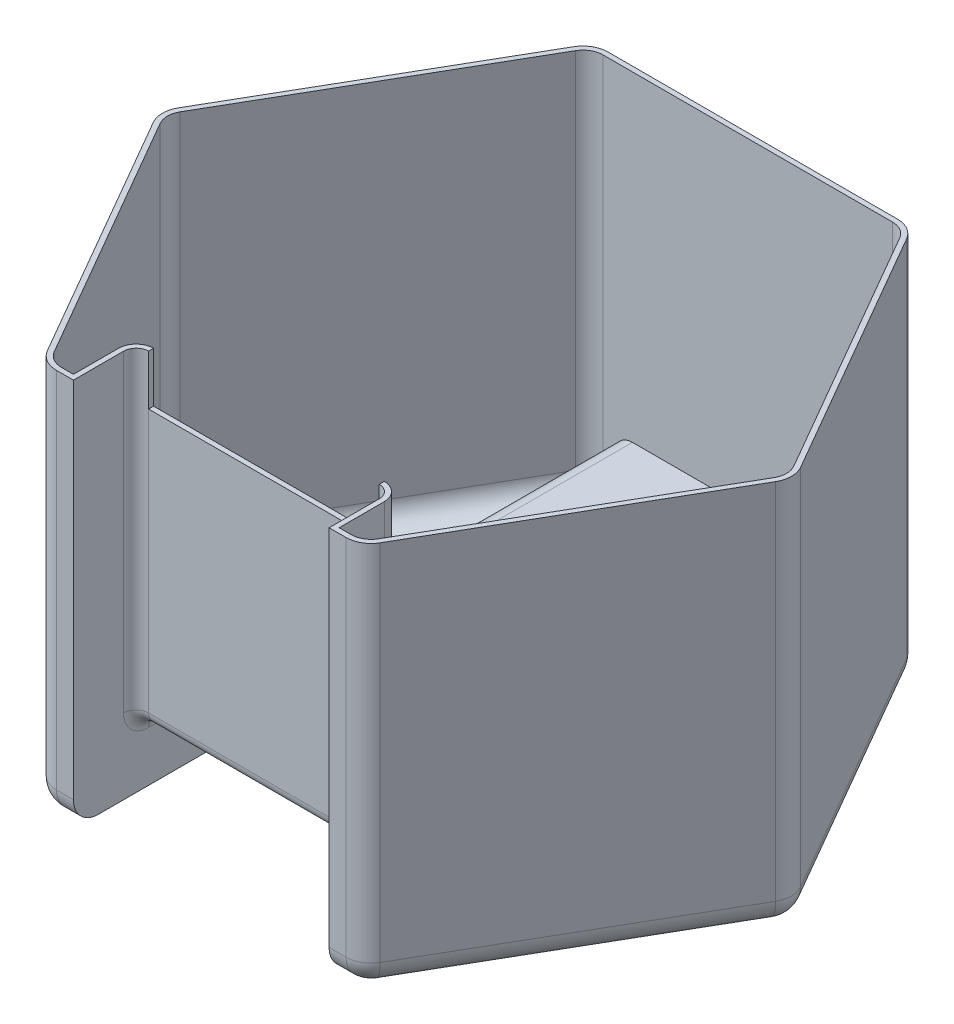
SolidWorks part; units mm, degrees
ref_plane "Front Plane" through (0, 0, 0) normal (0, 0, 1) x (1, 0, 0)
ref_plane "Top Plane" through (0, 0, 0) normal (0, 1, 0) x (1, 0, 0)
ref_plane "Right Plane" through (0, 0, 0) normal (1, 0, 0) x (0, 0, -1)
sketch "Sketch1" plane through (0, 0, 0) normal (0, 1, 0) x (1, 0, 0)
  line L1 (63.5085, 110) -> (-63.5085, 110)
  line L2 (-63.5085, 110) -> (-127.0171, 0)
  line L3 (-127.0171, 0) -> (-63.5085, -110)
  line L4 (-63.5085, -110) -> (63.5085, -110)
  line L5 (63.5085, -110) -> (127.0171, 0)
  line L6 (127.0171, 0) -> (63.5085, 110)
  circle A0 centre (0, 0) radius 110 construction
  dimension "D1" = 220
extrude "Boss-Extrude1" add sketch "Sketch1" along normal blind 155
sketch "Sketch2" plane through (0, 155, 0) normal (0, 1, 0) x (1, 0, 0)
  line L0 (-63.5085, -110) -> (63.5085, -110) construction
  line L1 (-51, -110) -> (51, -110)
  line L2 (-51, -110) -> (-51, -85)
  line L3 (-51, -85) -> (51, -85)
  line L4 (51, -110) -> (51, -85)
  line L5 (-63.5085, -110) -> (-51, -110) construction
  line L6 (51, -110) -> (63.5085, -110) construction
  dimension "D1" = 102
  dimension "D2" = 25
extrude "Cut-Extrude1" cut sketch "Sketch2" against normal up to next
sketch "Sketch3" plane through (0, 0, 85) normal (0, 0, 1) x (1, 0, 0)
  line L0 (51, 0) -> (51, 155) construction
  line L1 (-51, 0) -> (51, 0)
  line L2 (-51, 0) -> (-51, 25)
  line L3 (-51, 25) -> (51, 25)
  line L4 (51, 0) -> (51, 25)
  dimension "D1" = 25
extrude "Cut-Extrude2" cut sketch "Sketch3" against normal up to next
fillet "Fillet1" radius 5 5 edges at (51, 25, -12.5) (-51, 25, -12.5) (51, 90, 85) (0, 25, 85) (-51, 90, 85)
fillet "Fillet2" radius 10 6 edges at (63.5085, 77.5, 110) (127.0171, 77.5, 0) (63.5085, 77.5, -110) (-63.5085, 77.5, -110) (-127.0171, 77.5, 0) (-63.5085, 77.5, 110)
fillet "Fillet4" radius 10 14 edges at (125.4701, 0, 0) (95.2628, 0, -55) (95.2628, 0, 55) (-125.4701, 0, 0) (-95.2628, 0, 55) (-95.2628, 0, -55) (-54.3675, 0, -110) (-62.735, 0, -108.6603) (-54.3675, 0, 110) (-62.735, 0, 108.6603) (54.3675, 0, 110) (62.735, 0, 108.6603) (54.3675, 0, -110) (62.735, 0, -108.6603)
shell "Shell1" thickness 2
sketch "Sketch9" plane through (0, 0, 85) normal (0, 0, 1) x (1, 0, 0)
  line L0 (46, 30) -> (46, 155) construction
  line L1 (-46, 155) -> (46, 155)
  line L2 (-46, 155) -> (-46, 135)
  line L3 (-46, 135) -> (46, 135)
  line L4 (46, 155) -> (46, 135)
  dimension "D1" = 20
extrude "Cut-Extrude3" cut sketch "Sketch9" against normal up to next
